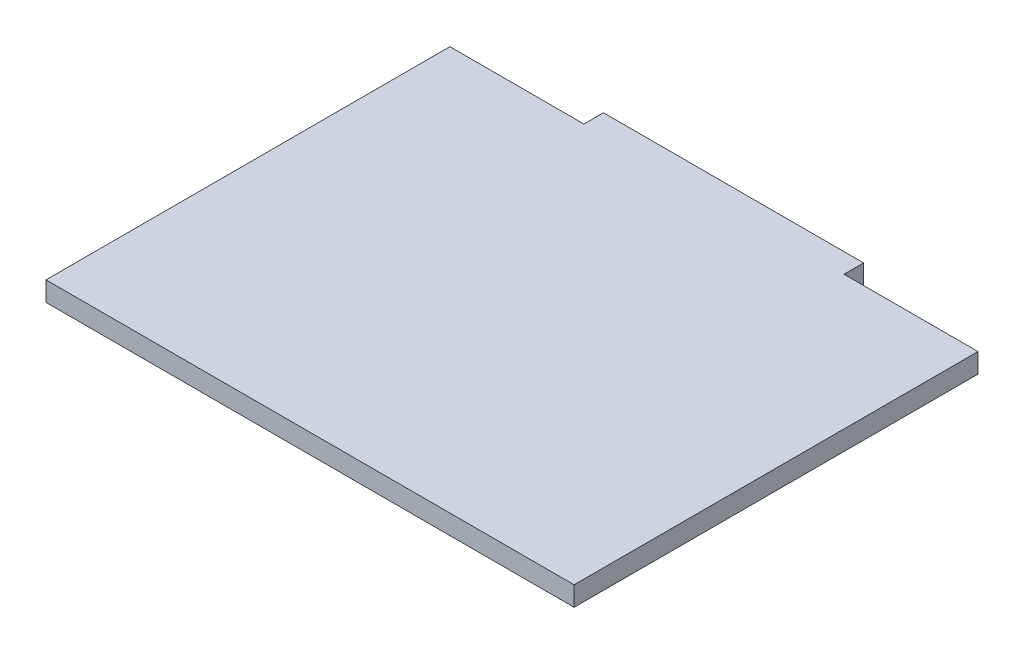
SolidWorks part; units mm, degrees
material "PPS"
ref_plane "Front Plane" through (0, 0, 0) normal (0, 0, 1) x (1, 0, 0)
ref_plane "Top Plane" through (0, 0, 0) normal (0, 1, 0) x (1, 0, 0)
ref_plane "Right Plane" through (0, 0, 0) normal (1, 0, 0) x (0, 0, -1)
sketch "Sketch1" plane through (0, 0, 0) normal (0, 1, 0) x (1, 0, 0)
  line L1 (0, 0) -> (40.5, 0)
  line L2 (0, 0) -> (0, 30.975)
  line L3 (10.275, 32.475) -> (30.225, 32.475)
  line L4 (40.5, 0) -> (40.5, 30.975)
  line L7 (0, 30.975) -> (10.275, 30.975)
  line L8 (10.275, 32.475) -> (10.275, 30.975)
  line L11 (40.5, 30.975) -> (30.225, 30.975)
  line L12 (30.225, 32.475) -> (30.225, 30.975)
  dimension "D1" = 40.5
  dimension "D2" = 1.5
  dimension "D3" = 19.95
  dimension "D4" = 30.975
extrude "Boss-Extrude1" add sketch "Sketch1" along normal blind 1.5
